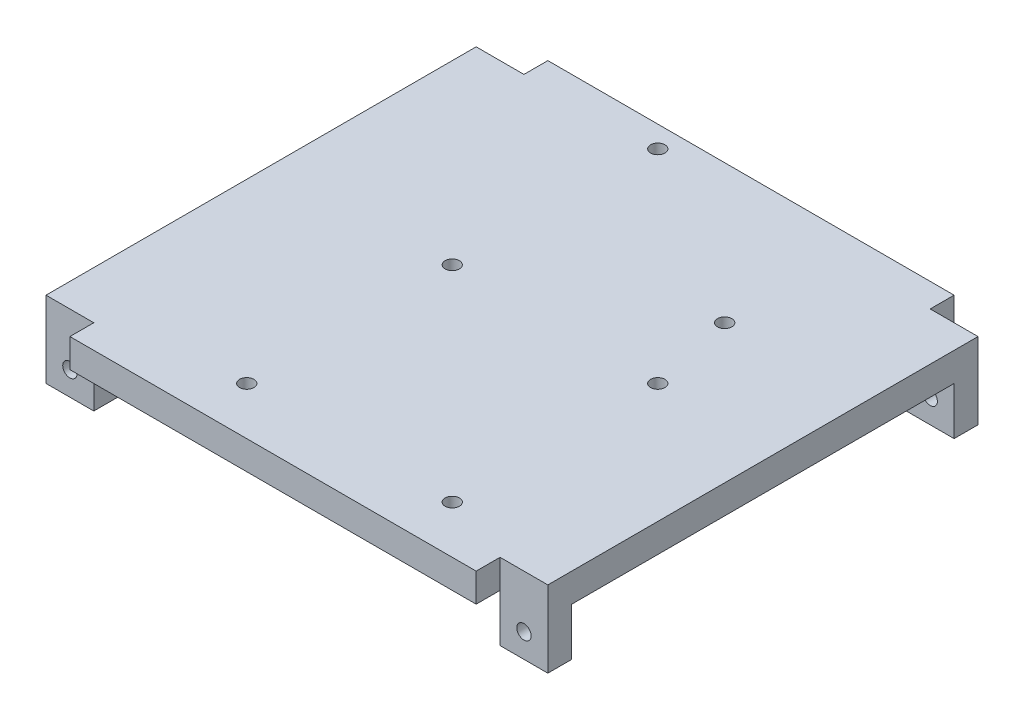
SolidWorks part; units mm, degrees
ref_plane "Front Plane" through (0, 0, 0) normal (0, 0, 1) x (1, 0, 0)
ref_plane "Top Plane" through (0, 0, 0) normal (0, 1, 0) x (1, 0, 0)
ref_plane "Right Plane" through (0, 0, 0) normal (1, 0, 0) x (0, 0, -1)
sketch "Sketch1" plane through (0, 0, 0) normal (0, 1, 0) x (1, 0, 0)
  line L1 (0, 0) -> (105, 0)
  line L2 (0, 0) -> (0, 100)
  line L3 (0, 100) -> (105, 100)
  line L4 (105, 0) -> (105, 100)
  dimension "D1" = 105
  dimension "D2" = 100
extrude "Boss-Extrude1" add sketch "Sketch1" along normal blind 6
sketch "Sketch2" plane through (0, 0, 0) normal (0, -1, 0) x (1, 0, 0)
  line L1 (105, -100) -> (95, -100)
  line L2 (105, -100) -> (105, -95)
  line L3 (105, -95) -> (95, -95)
  line L4 (95, -100) -> (95, -95)
  line L5 (0, -100) -> (10, -100)
  line L6 (0, -100) -> (0, -95)
  line L7 (0, -95) -> (10, -95)
  line L8 (10, -100) -> (10, -95)
  line L9 (105, 0) -> (95, 0)
  line L10 (105, 0) -> (105, -5)
  line L11 (105, -5) -> (95, -5)
  line L12 (95, 0) -> (95, -5)
  line L13 (0, 0) -> (10, 0)
  line L14 (0, 0) -> (0, -5)
  line L15 (0, -5) -> (10, -5)
  line L16 (10, 0) -> (10, -5)
  dimension "D1" = 10
  dimension "D2" = 5
extrude "Cut-Extrude1" cut sketch "Sketch2" against normal blind 10
sketch "Sketch3" plane through (0, 0, 0) normal (0, -1, 0) x (-1, 0, 0)
  line L1 (-105, 95) -> (-95, 95)
  line L2 (-105, 95) -> (-105, 90)
  line L3 (-105, 90) -> (-95, 90)
  line L4 (-95, 95) -> (-95, 90)
  line L5 (-105, 5) -> (-95, 5)
  line L6 (-105, 5) -> (-105, 10)
  line L7 (-105, 10) -> (-95, 10)
  line L8 (-95, 5) -> (-95, 10)
  line L9 (0, 5) -> (-10, 5)
  line L10 (0, 5) -> (0, 10)
  line L11 (0, 10) -> (-10, 10)
  line L12 (-10, 5) -> (-10, 10)
  line L13 (0, 95) -> (-10, 95)
  line L14 (0, 95) -> (0, 90)
  line L15 (0, 90) -> (-10, 90)
  line L16 (-10, 95) -> (-10, 90)
  dimension "D1" = 10
  dimension "D2" = 5
extrude "Boss-Extrude2" add sketch "Sketch3" along normal blind 10
sketch "Sketch4" plane through (0, 0, -95) normal (0, 0, -1) x (-1, 0, 0)
  line L0 (-105, 6) -> (-105, -10) construction
  line L1 (-95, -10) -> (-105, -10) construction
  line L2 (0, -10) -> (-10, -10) construction
  line L3 (-10, -10) -> (-10, 0) construction
  circle A0 centre (-100, -5) radius 1.5
  circle A1 centre (-5, -5) radius 1.5
  dimension "D1" = 5
  dimension "D2" = 5
  dimension "D3" = 3
  dimension "D4" = 5
  dimension "D5" = 5
extrude "Cut-Extrude2" cut sketch "Sketch4" against normal through all
sketch "Sketch5" plane through (0, 0, 0) normal (0, -1, 0) x (-1, 0, 0)
  line L0 (-10, 0) -> (-95, 0) construction
  line L1 (-105, 10) -> (-105, 90) construction
  circle A0 centre (-37, 10) radius 1.5
  circle A1 centre (-37, 53) radius 1.5
  circle A2 centre (-80, 53) radius 1.5
  circle A3 centre (-80, 10) radius 1.5
  dimension "D2" = 25
  dimension "D3" = 43
  dimension "D4" = 43
  dimension "D5" = 3
  dimension "D1" = 10
extrude "Cut-Extrude4" cut sketch "Sketch5" against normal blind 6
sketch "Sketch6" plane through (0, 0, 0) normal (0, -1, 0) x (-1, 0, 0)
  line L3 (-105, 10) -> (-105, 90) construction
  circle A0 centre (-37.5, 95.5) radius 1.5
  circle A1 centre (-76, 71) radius 1.5
  circle A2 centre (-80, 53) radius 1.5 construction
  dimension "D1" = 24.5
  dimension "D2" = 3
  dimension "D3" = 38.5
  dimension "D4" = 18
  dimension "D5" = 29
extrude "Cut-Extrude5" cut sketch "Sketch6" against normal blind 6
